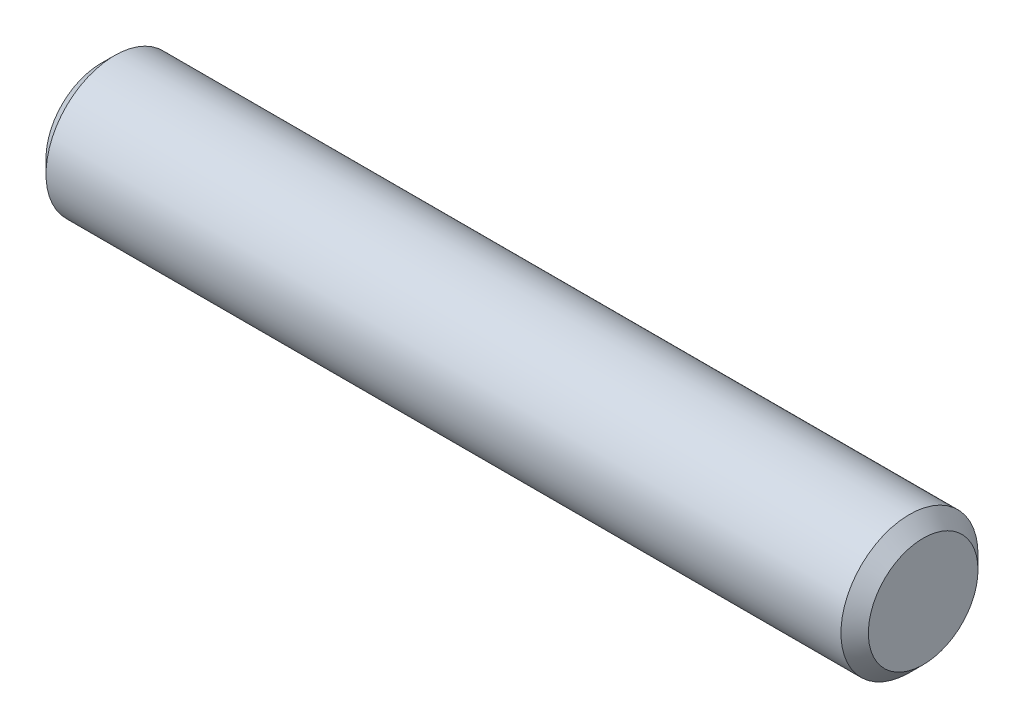
SolidWorks part; units mm, degrees
material "Plain Carbon Steel"
ref_plane "Front" through (0, 0, 0) normal (0, 0, 1) x (1, 0, 0)
ref_plane "Top" through (0, 0, 0) normal (0, 1, 0) x (1, 0, 0)
ref_plane "Right" through (0, 0, 0) normal (1, 0, 0) x (0, 0, -1)
sketch "Sketch1" plane through (0, 0, 0) normal (0, 0, 1) x (1, 0, 0)
  line L0 (-9.525, 0) -> (9.525, 0) construction
  line L1 (9.525, 1.5875) -> (9.525, -1.5875) construction
  line L2 (-9.525, 1.5875) -> (-9.525, -1.5875) construction
  dimension "Length" = 19.05
  dimension "Diameter" = 3.175
sketch "Sketch2" plane through (0, 0, 0) normal (1, 0, 0) x (0, 0, -1)
  circle A0 centre (0, 0) radius 1.5875
extrude "Extrude1" add sketch "Sketch2" against normal up to vertex (9.525 mm away) and the other way up to vertex (9.525 mm away) up to point (-9.525, 1.5875, 0) other way up to point (9.525, 1.5875, 0)
chamfer "Chamfer1" distance 0.3175 angle 45 2 edges at (9.525, 0, -1.5875) (-9.525, 0, -1.5875)
equation "\"D1@Chamfer1\" = \"Diameter@Sketch1\"*.1"
